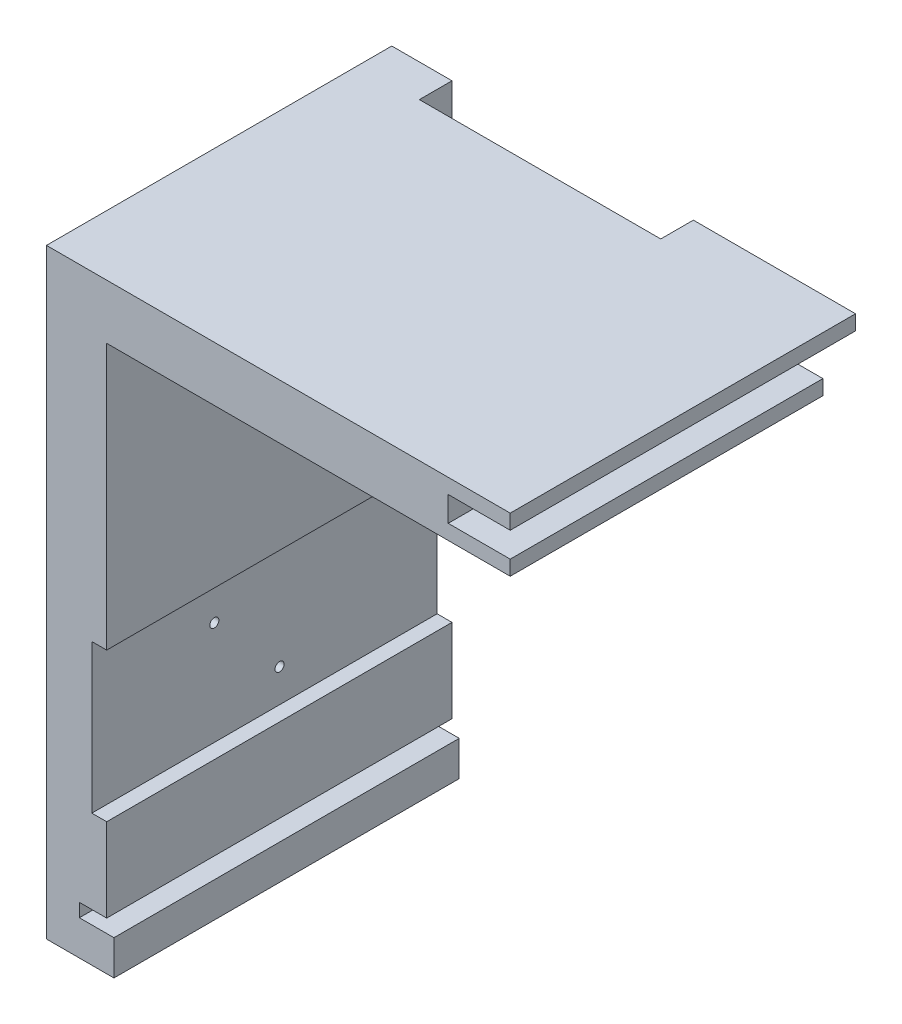
SolidWorks part; units mm, degrees
ref_plane "Front Plane" through (0, 0, 0) normal (0, 0, 1) x (1, 0, 0)
ref_plane "Top Plane" through (0, 0, 0) normal (0, 1, 0) x (1, 0, 0)
ref_plane "Right Plane" through (0, 0, 0) normal (1, 0, 0) x (0, 0, -1)
sketch "Sketch1" plane through (0, 0, 0) normal (0, 0, 1) x (1, 0, 0)
  line L0 (0, 0) -> (-111.31, 0)
  line L1 (0, 0) -> (0, 4.1)
  line L2 (0, 4.1) -> (-17.1, 4.1)
  line L3 (-17.1, 4.1) -> (-17.1, 10.99)
  line L4 (-17.1, 10.99) -> (0, 10.99)
  line L5 (0, 10.99) -> (0, 15.09)
  line L6 (0, 15.09) -> (-127.92, 15.09)
  line L7 (-127.92, 15.09) -> (-127.92, -150.62)
  line L8 (-127.92, -150.62) -> (-109.31, -150.62)
  line L9 (-109.31, -150.62) -> (-109.31, -140.99)
  line L10 (-109.31, -140.99) -> (-118.84, -140.99)
  line L11 (-118.84, -140.99) -> (-118.84, -137.31)
  line L12 (-118.84, -137.31) -> (-111.31, -137.31)
  line L13 (-111.31, -137.31) -> (-111.31, -114.29)
  line L14 (-111.31, -114.29) -> (-115.41, -114.29)
  line L15 (-115.41, -114.29) -> (-115.41, -73.29)
  line L16 (-115.41, -73.29) -> (-111.31, -73.29)
  line L17 (-111.31, 0) -> (-111.31, -73.29)
  dimension "D1" = 165.71
  dimension "D2" = 73.29
  dimension "D3" = 4.1
  dimension "D4" = 17.1
  dimension "D5" = 6.89
  dimension "D6" = 127.92
  dimension "D7" = 18.61
  dimension "D8" = 9.63
  dimension "D9" = 9.53
  dimension "D10" = 7.53
  dimension "D11" = 23.02
  dimension "D12" = 4.1
  dimension "D13" = 41
extrude "Boss-Extrude1" add sketch "Sketch1" along normal blind 95.25 contours L7 L8 L9 L10 L11 L12 L13 L14 L15 L16 L17 L0 L1 L2 L3 L4 L5 L6
sketch "Sketch4" plane through (0, 0, 0) normal (0, 0, -1) x (-1, 0, 0)
  line L0 (111.31, 0) -> (0, 0)
  line L1 (0, 0) -> (0, 10.99)
  line L4 (0, 10.99) -> (44.73, 10.99)
  line L5 (44.73, 10.99) -> (44.73, 15.09)
  line L6 (0, 15.09) -> (127.92, 15.09) construction
  line L7 (111.31, 0) -> (111.31, 15.09)
  line L8 (111.31, 15.09) -> (44.73, 15.09)
  dimension "D1" = 66.58
extrude "Cut-Extrude1" cut sketch "Sketch4" against normal blind 9
sketch "Sketch5" plane through (-115.41, 0, 0) normal (1, 0, 0) x (0, 0, -1)
  line L0 (-95.25, -114.29) -> (-95.25, -73.29) construction
  line L1 (-95.25, -114.29) -> (0, -114.29) construction
  circle A0 centre (-43.46, -105.21) radius 1.25
  circle A1 centre (-61.46, -85.71) radius 1.25
  dimension "D1" = 2.5
  dimension "D2" = 33.79
  dimension "D3" = 18
  dimension "D4" = 19.5
  dimension "D5" = 9.08
extrude "Cut-Extrude2" cut sketch "Sketch5" against normal blind 3
